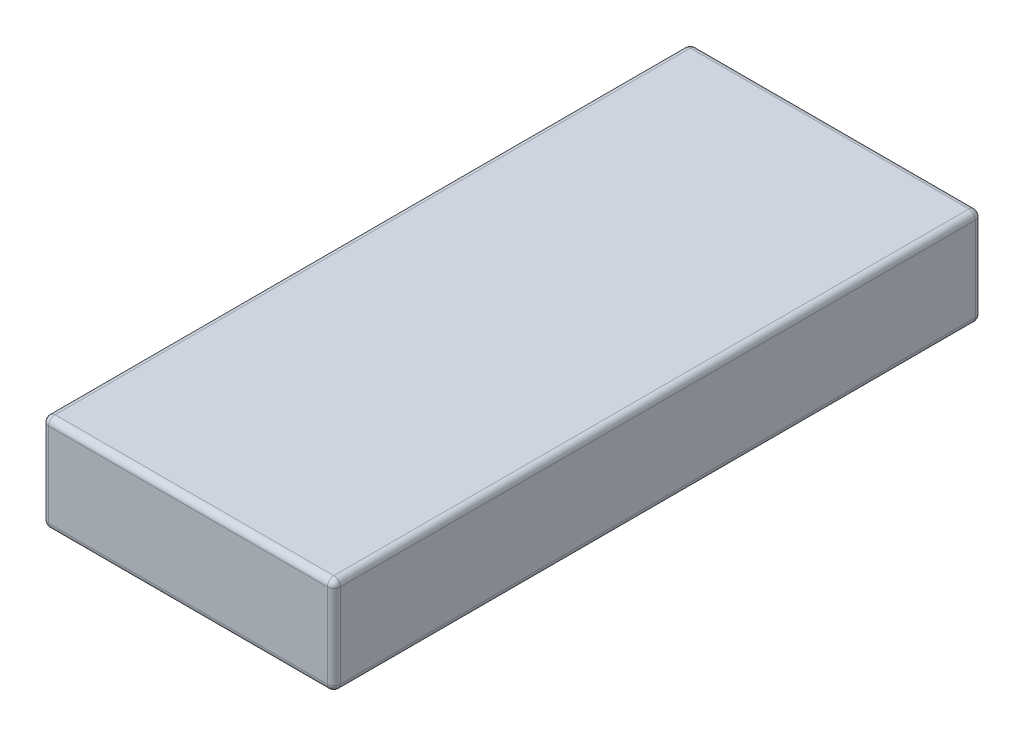
SolidWorks part; units mm, degrees
ref_plane "Front Plane" through (0, 0, 0) normal (0, 0, 1) x (1, 0, 0)
ref_plane "Top Plane" through (0, 0, 0) normal (0, 1, 0) x (1, 0, 0)
ref_plane "Right Plane" through (0, 0, 0) normal (1, 0, 0) x (0, 0, -1)
sketch "Sketch1" plane through (0, 0, 0) normal (0, 1, 0) x (1, 0, 0)
  line L1 (-450, 1000) -> (450, 1000)
  line L2 (-450, 1000) -> (-450, -1000)
  line L3 (-450, -1000) -> (450, -1000)
  line L4 (450, 1000) -> (450, -1000)
  line L5 (-450, 1000) -> (450, -1000) construction
  line L6 (-450, -1000) -> (450, 1000) construction
  point P0 (0, 0)
  dimension "D1" = 2000
  dimension "D2" = 900
extrude "Boss-Extrude1" add sketch "Sketch1" along normal blind 300
fillet "Fillet1" radius 20 12 edges at (0, 0, 1000) (-450, 0, 0) (0, 0, -1000) (450, 0, 0) (450, 150, -1000) (-450, 150, -1000) (0, 300, -1000) (-450, 300, 0) (-450, 150, 1000) (450, 150, 1000) (0, 300, 1000) (450, 300, 0)
